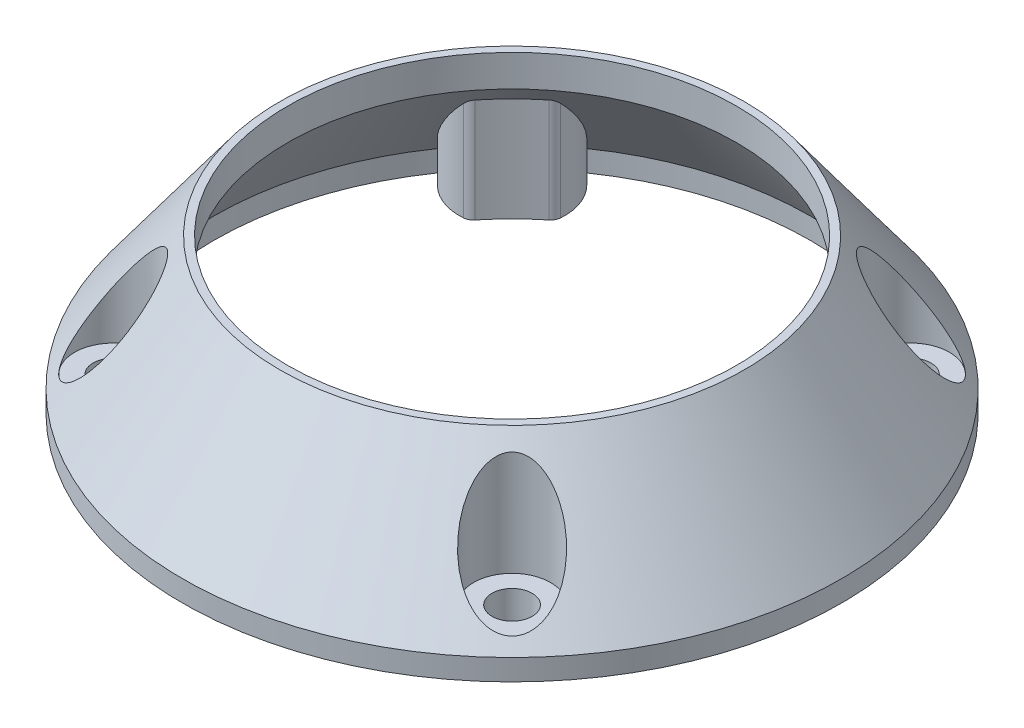
SolidWorks part; units mm, degrees
material "6061-T6 (SS)"
ref_plane "Front Plane" through (0, 0, 0) normal (0, 0, 1) x (1, 0, 0)
ref_plane "Top Plane" through (0, 0, 0) normal (0, 1, 0) x (1, 0, 0)
ref_plane "Right Plane" through (0, 0, 0) normal (1, 0, 0) x (0, 0, -1)
sketch "Sketch3" plane through (0, 0, 0) normal (0, 0, 1) x (1, 0, 0)
  line L0 (0, -74.5829) -> (0, 74.5829) construction
  line L10 (-21.1173, 0) -> (56.8383, 0) construction
  line L11 (35.89, 0) -> (27, 12.0946)
  line L12 (27, 12.0946) -> (27, 17.1746)
  line L13 (27, 17.1746) -> (39.624, 0)
  line L15 (35.89, 0) -> (35.89, -2.54)
  line L16 (35.89, -2.54) -> (39.624, -2.54)
  line L17 (39.624, -2.54) -> (39.624, 0)
  dimension "D1" = 12.0946
  dimension "D2" = 27
  dimension "D3" = 2.54
  dimension "D4" = 5.08
  dimension "D5" = 8.89
revolve "Revolve1" add sketch "Sketch3" angle 360 about L0
sketch "Sketch4" plane through (0, -2.54, 0) normal (0, -1, 0) x (1, 0, 0)
  line L0 (0, -53.6346) -> (0, 53.6346) construction
  line L1 (-50.2847, 0) -> (55.027, 0) construction
  line L2 (-19.2177, 28.198) -> (-20.4876, 29.4678)
  line L7 (-23.7079, -23.7079) -> (23.7079, -23.7079) construction
  line L8 (-23.7079, -23.7079) -> (-23.7079, 23.7079) construction
  line L9 (-23.7079, 23.7079) -> (23.7079, 23.7079) construction
  line L10 (23.7079, -23.7079) -> (23.7079, 23.7079) construction
  line L11 (-23.7079, -23.7079) -> (23.7079, 23.7079) construction
  line L12 (-23.7079, 23.7079) -> (23.7079, -23.7079) construction
  line L13 (-28.198, 19.2177) -> (-29.4678, 20.4876)
  line L14 (-28.198, 19.2177) -> (-19.2177, 28.198) construction
  line L15 (28.198, 19.2177) -> (19.2177, 28.198) construction
  line L16 (28.198, 19.2177) -> (29.4678, 20.4876)
  line L17 (19.2177, 28.198) -> (20.4876, 29.4678)
  line L18 (28.198, -19.2177) -> (19.2177, -28.198) construction
  line L19 (-28.198, -19.2177) -> (-19.2177, -28.198) construction
  line L20 (-23.7079, -23.7079) -> (23.7079, -23.7079) construction
  line L21 (19.2177, -28.198) -> (20.4876, -29.4678)
  line L22 (28.198, -19.2177) -> (29.4678, -20.4876)
  line L23 (-28.198, -19.2177) -> (-29.4678, -20.4876)
  line L24 (-19.2177, -28.198) -> (-20.4876, -29.4678)
  arc A0 (-28.198, 19.2177) -> (-22.6277, 17.4504) centre (-23.7079, 23.7079) ccw
  circle A1 centre (0, 0) radius 35.89 construction
  arc A2 (-22.6277, -17.4504) -> (-17.4504, -22.6277) centre (0, 0) ccw
  arc A3 (-17.4504, -22.6277) -> (-19.2177, -28.198) centre (-23.7079, -23.7079) cw
  arc A5 (-20.4876, 29.4678) -> (-29.4678, 20.4876) centre (0, 0) ccw
  arc A7 (20.4876, 29.4678) -> (29.4678, 20.4876) centre (0, 0) cw
  arc A8 (28.198, 19.2177) -> (22.6277, 17.4504) centre (23.7079, 23.7079) cw
  arc A9 (28.198, -19.2177) -> (22.6277, -17.4504) centre (23.7079, -23.7079) ccw
  arc A10 (20.4876, -29.4678) -> (29.4678, -20.4876) centre (0, 0) ccw
  arc A11 (-20.4876, -29.4678) -> (-29.4678, -20.4876) centre (0, 0) cw
  arc A12 (-28.198, -19.2177) -> (-22.6277, -17.4504) centre (-23.7079, -23.7079) cw
  arc A13 (17.4504, -22.6277) -> (22.6277, -17.4504) centre (0, 0) ccw
  arc A14 (17.4504, -22.6277) -> (19.2177, -28.198) centre (23.7079, -23.7079) ccw
  arc A15 (22.6277, 17.4504) -> (17.4504, 22.6277) centre (0, 0) ccw
  arc A16 (17.4504, 22.6277) -> (19.2177, 28.198) centre (23.7079, 23.7079) cw
  arc A17 (-17.4504, 22.6277) -> (-22.6277, 17.4504) centre (0, 0) ccw
  arc A18 (-17.4504, 22.6277) -> (-19.2177, 28.198) centre (-23.7079, 23.7079) ccw
  point P5 (0, 0)
  point P6 (0, 0)
  dimension "D2" = 12.7
  dimension "D1" = 67.056
extrude "Boss-Extrude2" add sketch "Sketch4" against normal up to surface (12.4918 mm away)
sketch "Sketch6" plane through (0, -2.54, 0) normal (0, -1, 0) x (1, 0, 0)
  line L0 (0, -43.6677) -> (0, 46.4776) construction
  line L1 (-23.9773, -23.9773) -> (23.9773, -23.9773) construction
  line L2 (-23.9773, -23.9773) -> (-23.9773, 23.9773) construction
  line L3 (-23.9773, 23.9773) -> (23.9773, 23.9773) construction
  line L4 (23.9773, -23.9773) -> (23.9773, 23.9773) construction
  line L5 (-23.9773, -23.9773) -> (23.9773, 23.9773) construction
  line L6 (-23.9773, 23.9773) -> (23.9773, -23.9773) construction
  line L7 (-53.8984, 0) -> (50.6177, 0) construction
  circle A1 centre (-23.9773, 23.9773) radius 2.413
  circle A2 centre (23.9773, 23.9773) radius 2.413
  circle A3 centre (23.9773, -23.9773) radius 2.413
  circle A4 centre (-23.9773, -23.9773) radius 2.413
  point P0 (0, 0)
  dimension "D2" = 4.826
  dimension "D1" = 67.818
extrude "Cut-Extrude3" cut sketch "Sketch6" against normal through all
ref_plane "Plane2" through (0, 17.1746, 0) normal (0, 1, 0) x (1, 0, 0)
sketch "Sketch7" plane through (0, 17.1746, 0) normal (0, 1, 0) x (1, 0, 0)
  line L0 (0, -9.7335) -> (0, 8.8523) construction
  line L1 (-21.9329, 0) -> (14.1583, 0) construction
  circle A0 centre (-23.9773, 23.9773) radius 4.6355
  circle A1 centre (23.9773, 23.9773) radius 4.6355
  circle A2 centre (23.9773, -23.9773) radius 4.6355
  circle A3 centre (-23.9773, -23.9773) radius 4.6355
  point P17 (0, 0)
  dimension "D1" = 9.271
  dimension "D2" = 4
extrude "Cut-Extrude6" cut sketch "Sketch7" along a picked direction on the side against the normal blind 15.7234
sketch "Sketch8" plane through (0, 17.1746, 0) normal (0, 1, 0) x (1, 0, 0)
  circle A0 centre (0, 0) radius 51.3183
extrude "Cut-Extrude7" cut sketch "Sketch8" against normal blind 1.27
fillet "Fillet1" radius 1.27 8 edges at (22.6277, 3.7059, -17.4504) (17.4504, 3.7059, -22.6277) (-22.6277, 3.7059, -17.4504) (-17.4504, 3.7059, -22.6277) (-22.6277, 3.7059, 17.4504) (-17.4504, 3.7059, 22.6277) (17.4504, 3.7059, 22.6277) (22.6277, 3.7059, 17.4504)
